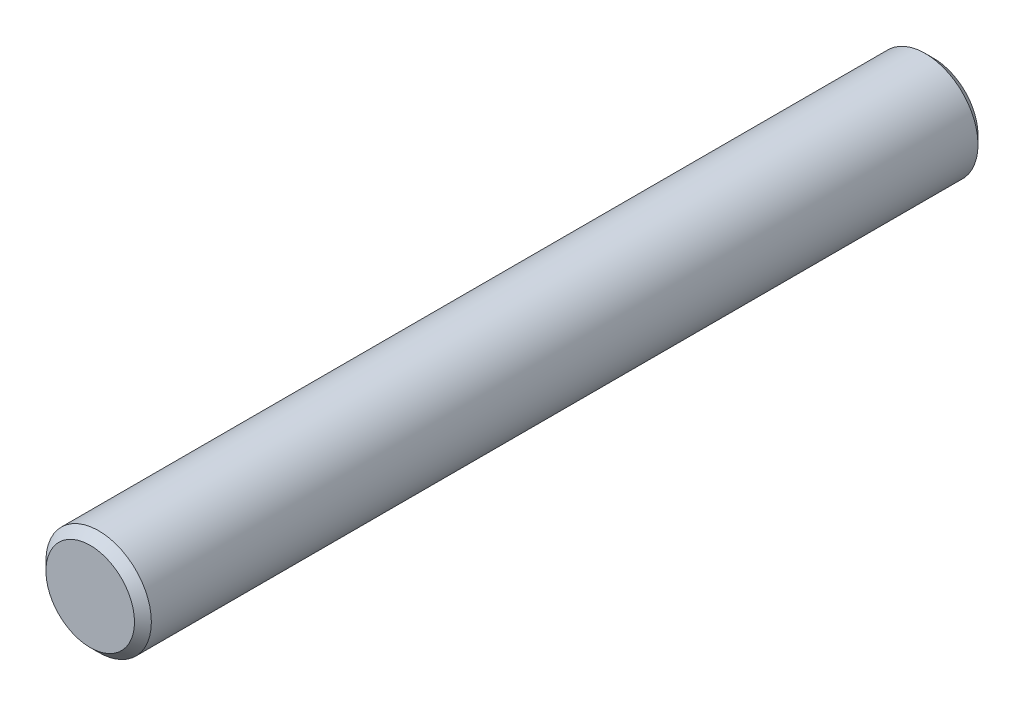
SolidWorks part; units mm, degrees
ref_plane "Front Plane" through (0, 0, 0) normal (0, 0, 1) x (1, 0, 0)
ref_plane "Top Plane" through (0, 0, 0) normal (0, 1, 0) x (1, 0, 0)
ref_plane "Right Plane" through (0, 0, 0) normal (1, 0, 0) x (0, 0, -1)
sketch "Sketch1" plane through (0, 0, 0) normal (0, 0, 1) x (1, 0, 0)
  circle A0 centre (0, 0) radius 12.5
  dimension "D1" = 25
extrude "Boss-Extrude1" add sketch "Sketch1" along normal blind 200
chamfer "Chamfer1" distance 2 angle 45 1 edges at (12.5, 0, 0)
chamfer "Chamfer2" distance 2 angle 45 1 edges at (12.5, 0, 200)
